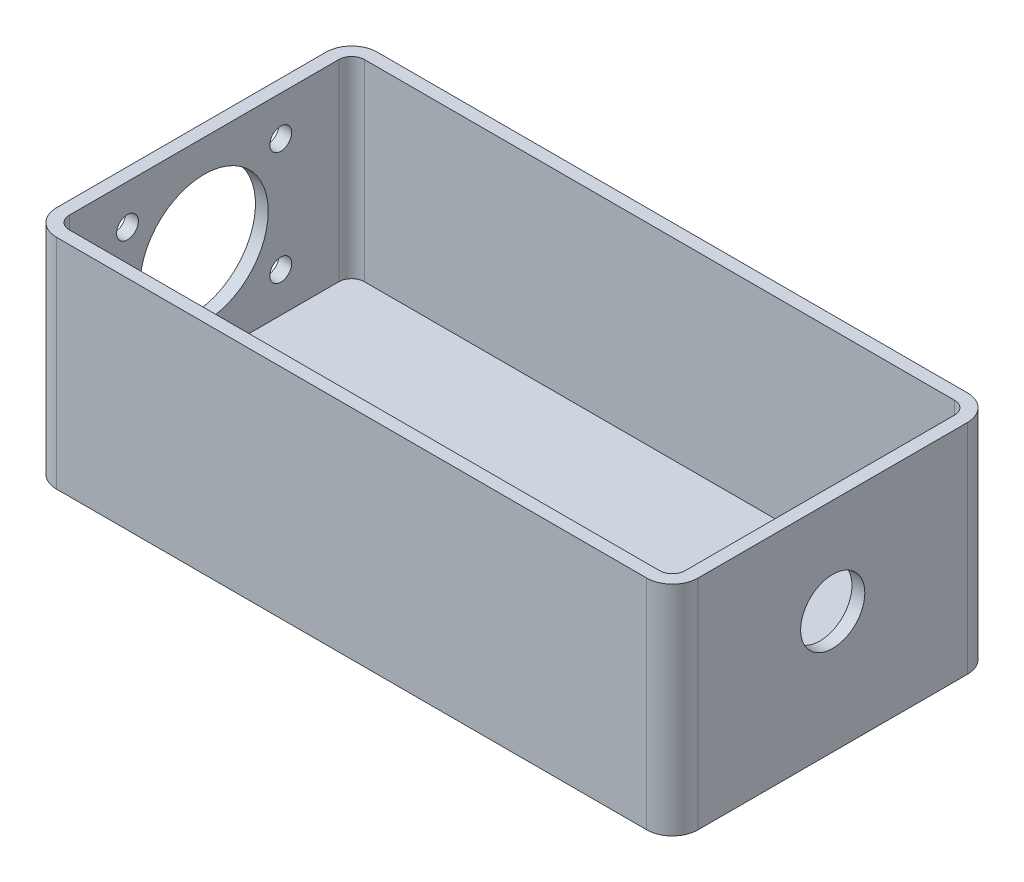
SolidWorks part; units mm, degrees
ref_plane "Front Plane" through (0, 0, 0) normal (0, 0, 1) x (1, 0, 0)
ref_plane "Top Plane" through (0, 0, 0) normal (0, 1, 0) x (1, 0, 0)
ref_plane "Right Plane" through (0, 0, 0) normal (1, 0, 0) x (0, 0, -1)
sketch "Sketch1" plane through (0, 0, 0) normal (0, 1, 0) x (1, 0, 0)
  line L1 (0, 0) -> (127, 0)
  line L2 (0, 0) -> (0, 63.5)
  line L3 (0, 63.5) -> (127, 63.5)
  line L4 (127, 0) -> (127, 63.5)
  dimension "D1" = 63.5
  dimension "D2" = 127
extrude "Boss-Extrude1" add sketch "Sketch1" along normal blind 5.08
sketch "Sketch2" plane through (0, 5.08, 0) normal (0, 1, 0) x (1, 0, 0)
  line L1 (0, 63.5) -> (127, 63.5)
  line L2 (0, 63.5) -> (0, 0)
  line L3 (0, 0) -> (127, 0)
  line L4 (127, 63.5) -> (127, 0)
  line L5 (2.54, 60.96) -> (124.46, 60.96)
  line L6 (2.54, 60.96) -> (2.54, 2.54)
  line L7 (2.54, 2.54) -> (124.46, 2.54)
  line L8 (124.46, 60.96) -> (124.46, 2.54)
  dimension "D1" = 2.54
  dimension "D2" = 2.54
  dimension "D3" = 2.54
  dimension "D4" = 2.54
extrude "Boss-Extrude3" add sketch "Sketch2" along normal blind 38.1
sketch "Sketch3" plane through (0, 0, 0) normal (-1, 0, 0) x (0, 0, 1)
  circle A0 centre (-31.75, 24.13) radius 12.7
  circle A1 centre (-46.9265, 35.3568) radius 2.159
  circle A2 centre (-16.5735, 35.3568) radius 2.159
  circle A3 centre (-46.9265, 12.9032) radius 2.159
  circle A4 centre (-16.5735, 12.9032) radius 2.159
  dimension "D1" = 25.4
  dimension "D2" = 4.318
  dimension "D3" = 4.318
  dimension "D4" = 4.318
  dimension "D5" = 4.318
  dimension "D6" = 30.353
  dimension "D7" = 22.4536
  dimension "D8" = 15.1765
  dimension "D9" = 11.2268
  dimension "D10" = 24.13
  dimension "D11" = 31.75
extrude "Cut-Extrude1" cut sketch "Sketch3" against normal up to next
sketch "Sketch4" plane through (127, 0, 0) normal (1, 0, 0) x (0, 0, -1)
  circle A1 centre (31.75, 24.13) radius 6.35
  dimension "D1" = 12.7
  dimension "D2" = 31.75
  dimension "D3" = 19.05
fillet "Fillet3" radius 5.08 4 edges at (0, 21.59, -63.5) (127, 21.59, -63.5) (127, 21.59, 0) (0, 21.59, 0)
fillet "Fillet4" radius 2.54 4 edges at (2.54, 24.13, -60.96) (2.54, 24.13, -2.54) (124.46, 24.13, -60.96) (124.46, 24.13, -2.54)
extrude "Cut-Extrude6" cut sketch "Sketch4" against normal up to next
